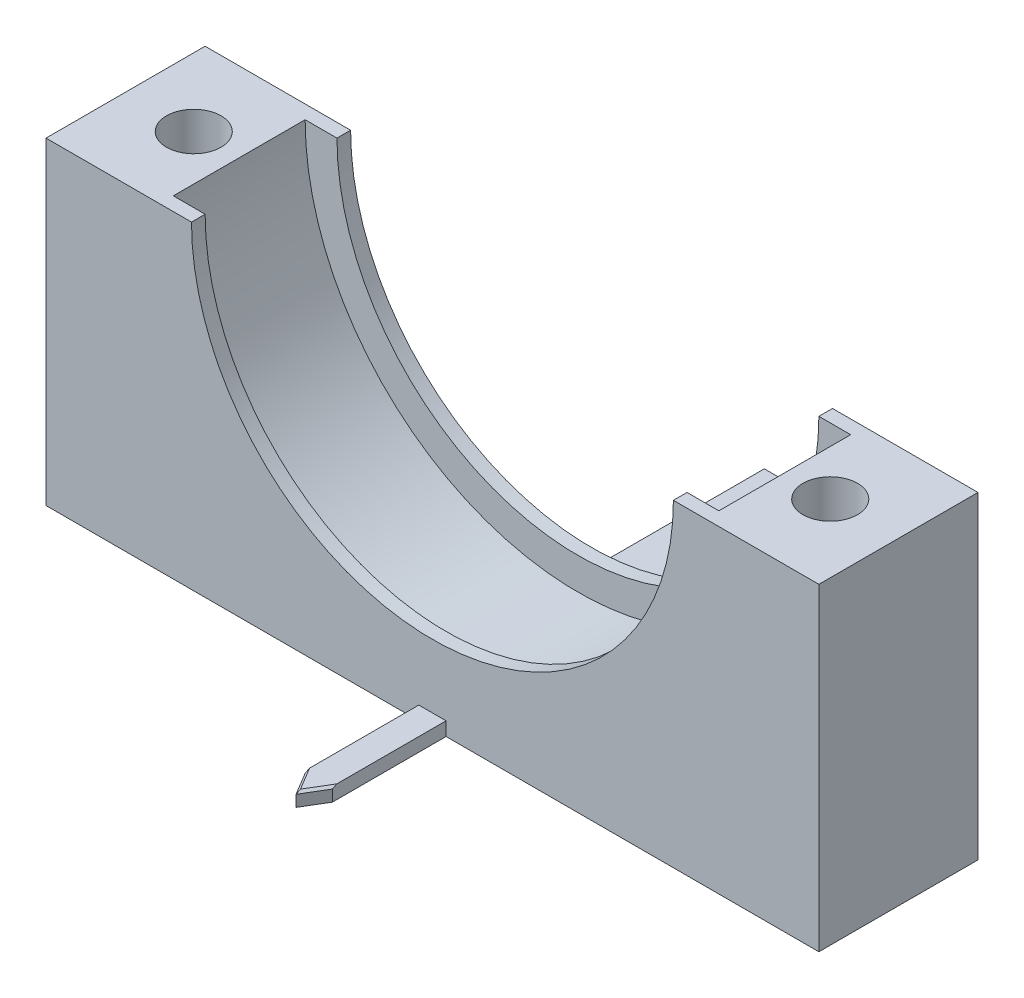
SolidWorks part; units mm, degrees
ref_plane "Płaszczyzna przednia" through (0, 0, 0) normal (0, 0, 1) x (1, 0, 0)
ref_plane "Płaszczyzna górna" through (0, 0, 0) normal (0, 1, 0) x (1, 0, 0)
ref_plane "Płaszczyzna prawa" through (0, 0, 0) normal (1, 0, 0) x (0, 0, -1)
sketch "Szkic1" plane through (0, 0, 0) normal (0, 0, 1) x (1, 0, 0)
  line L1 (-60, 0) -> (-85, 0)
  line L2 (-85, -30.5) -> (-85, -70)
  line L3 (-85, -70) -> (85, -70)
  line L4 (85, -70) -> (85, -30.5)
  line L10 (85, -30.5) -> (85, 0)
  line L12 (-85, 0) -> (-85, -30.5)
  line L13 (60, 0) -> (85, 0)
  arc A7 (60, 0) -> (-60, 0) centre (0, 0) cw
  point P41 (85, -32.5)
  point P42 (-85, -32.5)
  dimension "D2" = 25
extrude "Dodanie-wyciągnięcie1" add sketch "Szkic1" along normal mid plane 29
hole_wizard "Otwór Ø12.0 (12)1" positions "Szkic3" profile "Szkic2" hole size "Ø12.0" standard "DIN"
sketch "Szkic3" plane through (0, 0, 0) normal (0, 1, 0) x (1, 0, 0)
  line L0 (-85, -14.5) -> (-85, 14.5) construction
  line L1 (85, -14.5) -> (85, 14.5) construction
  point P0 (-70, 0)
  point P2 (70, 0)
  point P5 (-85, 0)
  point P8 (85, 0)
  dimension "D1" = 15
  dimension "D2" = 15
sketch "Szkic2" plane through (-70, 0, 0) normal (1, 0, 0) x (0, 0, 1)
  line L0 (0, 0) -> (0, 23.6052)
  line L1 (0, 23.6052) -> (6, 20)
  line L2 (6, 20) -> (6, 0)
  line L5 (6, 0) -> (0, 0)
  line L10 (0, 23.6052) -> (-6, 20) construction
  line L11 (0, -6.35) -> (0, 107.95) construction
  dimension "Średnica otworu" = 12
  dimension "Głębokość otworu" = 20
  dimension "Kąt wiertła" = 118
ref_point "Punkt1"
sketch "Szkic4" plane through (0, 0, -14.5) normal (0, 0, -1) x (-1, 0, 0)
  line L0 (-53, 0) -> (-85, 0)
  line L1 (-85, 0) -> (-85, -70)
  line L2 (-85, -70) -> (85, -70)
  line L3 (85, -70) -> (85, 0)
  line L4 (85, 0) -> (53, 0)
  arc A0 (-53, 0) -> (53, 0) centre (0, 0) ccw
  dimension "D1" = 106
extrude "Dodanie-wyciągnięcie2" add sketch "Szkic4" along normal blind 3
sketch "Szkic5" plane through (0, 0, 14.5) normal (0, 0, 1) x (1, 0, 0)
  line L0 (-53, 0) -> (-85, 0)
  line L1 (-85, 0) -> (-85, -70)
  line L2 (-85, -70) -> (85, -70)
  line L3 (85, -70) -> (85, 0)
  line L4 (85, 0) -> (53, 0)
  arc A0 (-53, 0) -> (53, 0) centre (0, 0) ccw
  dimension "D1" = 106
extrude "Dodanie-wyciągnięcie3" add sketch "Szkic5" along normal blind 3
sketch "Szkic6" plane through (0, -70, 0) normal (0, 1, 0) x (1, 0, 0)
  line L1 (85, 17.5) -> (-85, 17.5) construction
  line L2 (0, 17.5) -> (-10, 17.5)
  line L3 (0, 17.5) -> (10, 17.5)
  line L4 (-10, 17.5) -> (-10, 62.5)
  line L5 (10, 17.5) -> (10, 62.5)
  line L6 (-10, 62.5) -> (10, 62.5)
  dimension "D1" = 10
  dimension "D2" = 10
  dimension "D3" = 45
  dimension "D4" = 45
extrude "Dodanie-wyciągnięcie4" add sketch "Szkic6" along normal blind 3 contours L4 L6 L5 L3 L2
sketch "Szkic7" plane through (0, 0, -62.5) normal (0, 0, -1) x (-1, 0, 0)
  line L0 (-10, -67) -> (10, -67)
  line L1 (10, -67) -> (-10, -67) construction
  line L2 (10, -67) -> (10, -87)
  line L3 (10, -87) -> (-10, -87)
  line L4 (-10, -87) -> (-10, -67)
  dimension "D1" = 20
extrude "Dodanie-wyciągnięcie5" add sketch "Szkic7" along normal blind 3
sketch "Szkic8" plane through (0, -87, 0) normal (0, -1, 0) x (1, 0, 0)
  line L0 (-10, -65.5) -> (-10, -35.5)
  line L1 (-10, -65.5) -> (10, -65.5)
  line L2 (10, -65.5) -> (10, -35.5)
  line L3 (10, -35.5) -> (-10, -35.5)
  dimension "D1" = 30
extrude "Dodanie-wyciągnięcie6" add sketch "Szkic8" along normal blind 3
sketch "Szkic9" plane through (0, -90, 0) normal (0, -1, 0) x (1, 0, 0)
  circle A0 centre (0, -40.9973) radius 2
  dimension "D1" = 4
extrude "Wytnij-wyciągnięcie1" cut sketch "Szkic9" against normal blind 8 contours A0
sketch "Szkic10" plane through (0, -87, 0) normal (0, 1, 0) x (1, 0, 0)
  circle A0 centre (0, 40.9973) radius 4
  dimension "D1" = 8
extrude "Dodanie-wyciągnięcie7" add sketch "Szkic10" along normal blind 5
sketch "Szkic13" plane through (0, -82, 0) normal (0, 1, 0) x (1, 0, 0)
  circle A0 centre (0, 40.9973) radius 2
  dimension "D1" = 4
extrude "Wytnij-wyciągnięcie2" cut sketch "Szkic13" against normal blind 5
sketch "Szkic14" plane through (0, -70, 0) normal (0, 1, 0) x (1, 0, 0)
  line L0 (-3, -17.5) -> (-3, -42.5)
  line L2 (-3, -17.5) -> (3, -17.5)
  line L3 (-3, -42.5) -> (0, -47.5)
  line L4 (3, -42.5) -> (0, -47.5)
  line L6 (3, -42.5) -> (3, -17.5)
  dimension "D1" = 0
  dimension "D2" = 25
extrude "Dodanie-wyciągnięcie8" add sketch "Szkic14" along normal blind 3
chamfer "Sfazowanie1" distance 0.5 angle 45 2 edges at (-1.5, -67, 45) (1.5, -67, 45)
ref_plane "Płaszczyzna1" through (0, -67.5, 0) normal (0, 1, 0) x (1, 0, 0)
sketch "Szkic18" plane through (0, -70, 0) normal (0, -1, 0) x (-1, 0, 0)
  circle A0 centre (0, 0) radius 5
  dimension "D1" = 10
extrude "Dodanie-wyciągnięcie9" add sketch "Szkic18" along normal blind 10
chamfer "Sfazowanie2" distance 1 angle 45 1 edges at (0, -80, -5)
